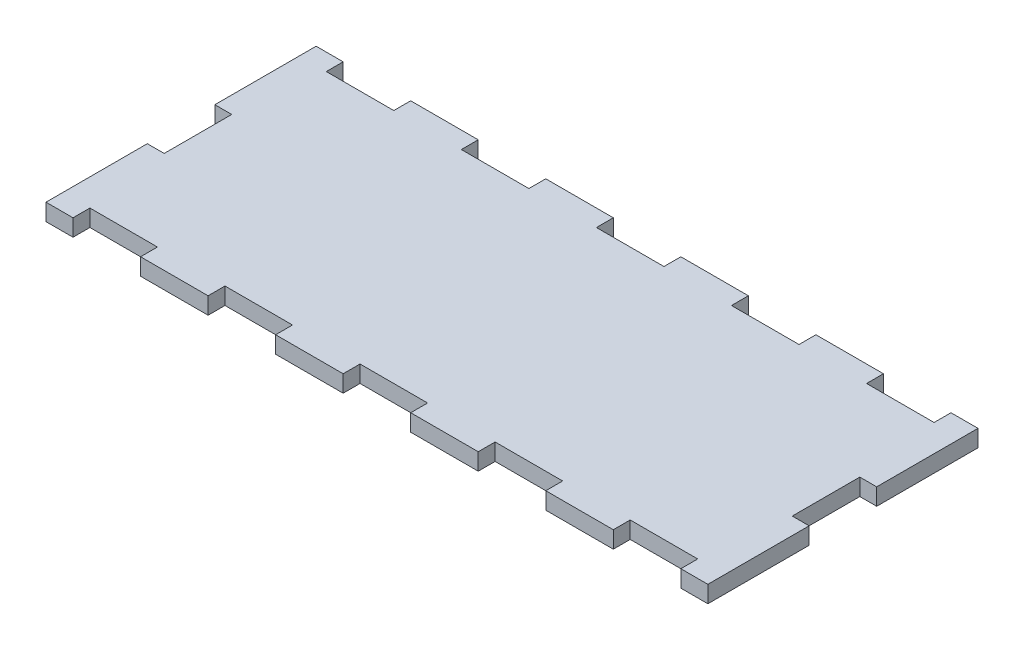
SolidWorks part; units mm, degrees
ref_plane "정면" through (0, 0, 0) normal (0, 0, 1) x (1, 0, 0)
ref_plane "윗면" through (0, 0, 0) normal (0, 1, 0) x (1, 0, 0)
ref_plane "우측면" through (0, 0, 0) normal (1, 0, 0) x (0, 0, -1)
sketch "스케치1" plane through (0, 0, 0) normal (0, 1, 0) x (1, 0, 0)
  line L1 (-98, 40) -> (98, 40)
  line L2 (-98, 40) -> (-98, -40)
  line L3 (-98, -40) -> (98, -40)
  line L4 (98, 40) -> (98, -40)
  line L5 (-98, 40) -> (98, -40) construction
  line L6 (-98, -40) -> (98, 40) construction
  point P0 (0, 0)
  dimension "D1" = 80
  dimension "D2" = 196
extrude "보스-돌출1" add sketch "스케치1" along normal blind 5
sketch "스케치2" plane through (0, 5, 0) normal (0, 1, 0) x (1, 0, 0)
  line L0 (-98, -40) -> (98, -40) construction
  line L1 (-10, -40) -> (10, -40)
  line L2 (-10, -40) -> (-10, -35)
  line L3 (-10, -35) -> (10, -35)
  line L4 (10, -40) -> (10, -35)
  line L5 (0, -8.0062) -> (0, -61.9938) construction
  point P9 (0, -35)
  dimension "D1" = 5
  dimension "D2" = 20
extrude "컷-돌출1" cut sketch "스케치2" against normal up to next
pattern_linear "선형 패턴1" count 3 spacing 40 along (1, 0, 0) of "컷-돌출1"
pattern_linear "선형 패턴2" count 3 spacing 40 along (-1, 0, 0) of "컷-돌출1"
sketch "스케치3" plane through (0, 5, 0) normal (0, 1, 0) x (1, 0, 0)
  line L0 (159.7454, 0) -> (81.4326, 0) construction
  line L1 (98, -10) -> (93, -10)
  line L2 (98, -10) -> (98, 10)
  line L3 (98, 10) -> (93, 10)
  line L4 (93, -10) -> (93, 10)
  line L5 (98, -40) -> (98, 40) construction
  point P9 (120.589, 0)
  dimension "D1" = 5
  dimension "D2" = 20
extrude "컷-돌출2" cut sketch "스케치3" against normal up to next
mirror "대칭 복사2" about plane through (0, 0, 0) normal (0, 0, 1) of "선형 패턴2", "선형 패턴1", "컷-돌출1"
mirror "대칭 복사3" about plane through (0, 0, 0) normal (1, 0, 0) of "컷-돌출2"
